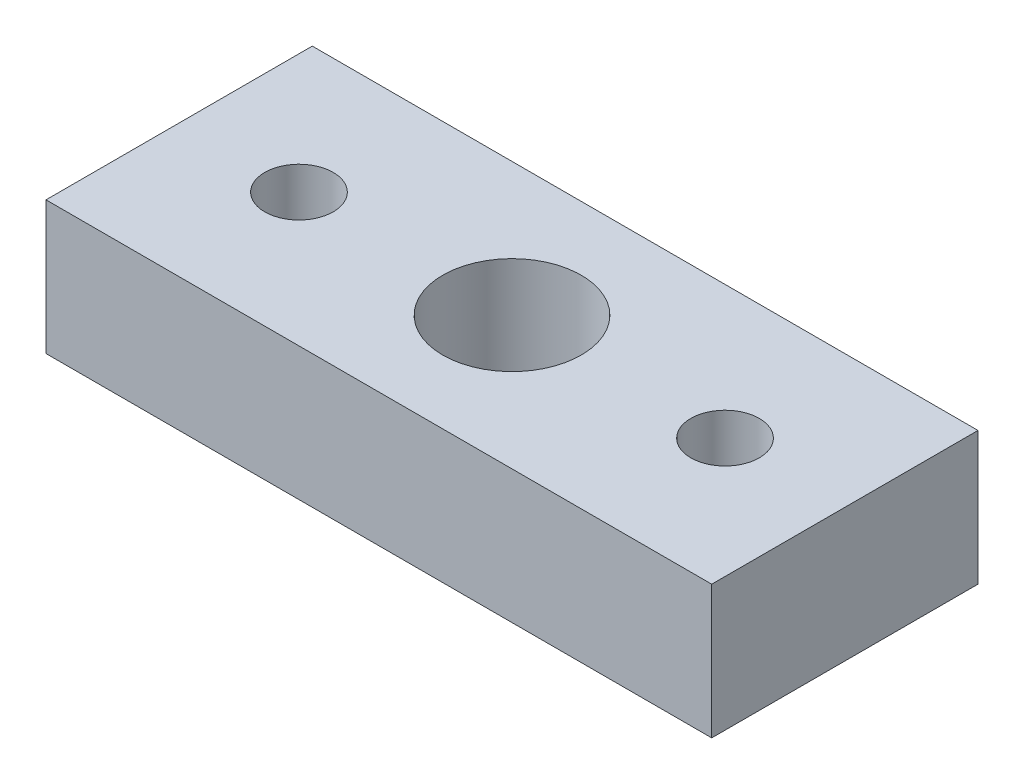
SolidWorks part; units mm, degrees
material "Beech"
ref_plane "Front Plane" through (0, 0, 0) normal (0, 0, 1) x (1, 0, 0)
ref_plane "Top Plane" through (0, 0, 0) normal (0, 1, 0) x (1, 0, 0)
ref_plane "Right Plane" through (0, 0, 0) normal (1, 0, 0) x (0, 0, -1)
sketch "Sketch1" plane through (0, 0, 0) normal (0, 1, 0) x (1, 0, 0)
  line L1 (-15.875, 6.35) -> (15.875, 6.35)
  line L2 (-15.875, 6.35) -> (-15.875, -6.35)
  line L3 (-15.875, -6.35) -> (15.875, -6.35)
  line L4 (15.875, 6.35) -> (15.875, -6.35)
  line L5 (-15.875, 6.35) -> (15.875, -6.35) construction
  line L6 (-15.875, -6.35) -> (15.875, 6.35) construction
  point P0 (0, 0)
  dimension "D1" = 31.75
  dimension "D2" = 12.7
extrude "Boss-Extrude1" add sketch "Sketch1" along normal blind 6.35
sketch "Sketch2" plane through (0, 6.35, 0) normal (0, 1, 0) x (1, 0, 0)
  circle A0 centre (0, 0) radius 3.302
  dimension "D1" = 6.604
extrude "Cut-Extrude1" cut sketch "Sketch2" against normal up to next contours A0
hole_wizard "#4 Clearance Hole1" positions "Sketch4" profile "Sketch3" hole size "#4" standard "ANSI Inch" end condition up to next
sketch "Sketch4" plane through (0, 6.35, 0) normal (0, 1, 0) x (1, 0, 0)
  line L4 (0, 0) -> (-10.16, 0) construction
  point P11 (-10.16, 0)
  dimension "D1" = 10.16
sketch "Sketch3" plane through (-10.16, 6.35, 0) normal (1, 0, 0) x (0, 0, 1)
  line L0 (0, 0) -> (0, 6.351)
  line L1 (0, 6.351) -> (1.6319, 6.351)
  line L2 (1.6319, 6.351) -> (1.6319, 0)
  line L5 (1.6319, 0) -> (0, 0)
  line L11 (0, -6.35) -> (0, 107.95) construction
  dimension "Thru Hole Dia." = 3.2639
  dimension "Thru Hole Depth" = 6.351
mirror "Mirror1" about plane through (0, 0, 0) normal (1, 0, 0) of "#4 Clearance Hole1"
